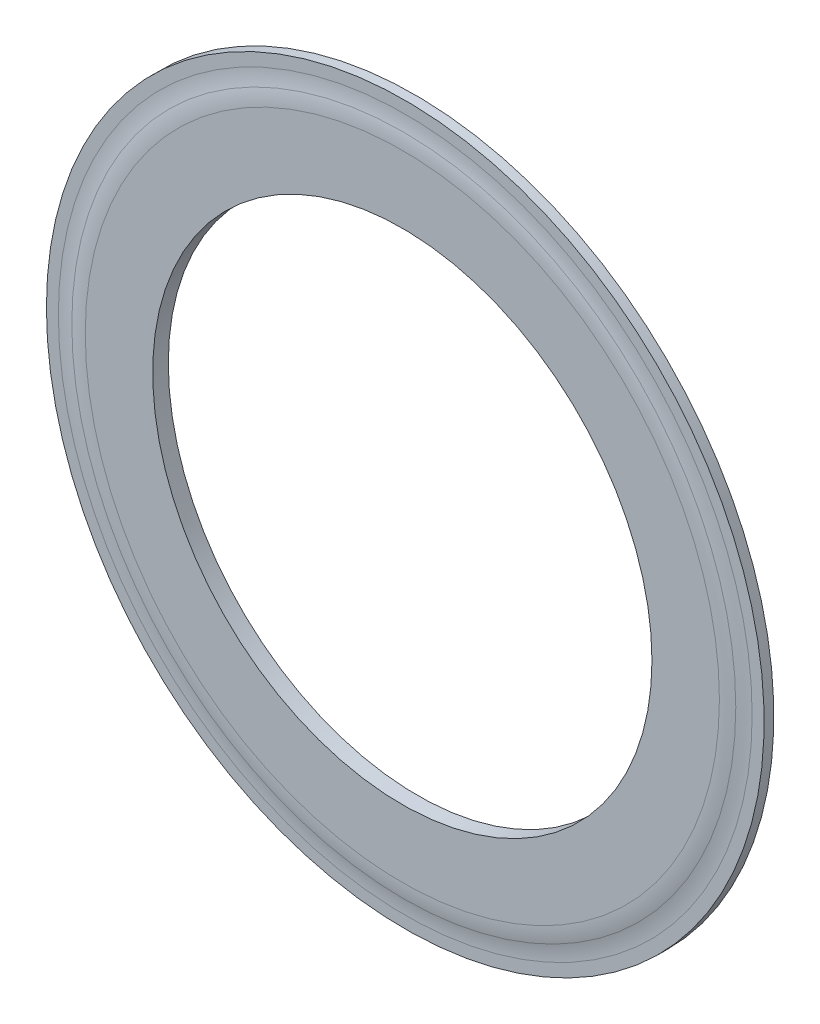
SolidWorks part; units mm, degrees
ref_plane "Front Plane" through (0, 0, 0) normal (0, 0, 1) x (1, 0, 0)
ref_plane "Top Plane" through (0, 0, 0) normal (0, 1, 0) x (1, 0, 0)
ref_plane "Right Plane" through (0, 0, 0) normal (1, 0, 0) x (0, 0, -1)
sketch "Sketch1" plane through (0, 0, 0) normal (0, 0, 1) x (1, 0, 0)
  line L0 (0, 36.5125) -> (0, -36.5125) construction
  line L1 (-36.5125, 0) -> (36.5125, 0) construction
  circle A0 centre (0, 0) radius 36.5125 construction
  circle A1 centre (0, 0) radius 16.2719 construction
  point P8 (0, -16.2719)
  point P9 (16.2719, 0)
  point P10 (0, 16.2719)
  point P11 (-16.2719, 0)
  point P13 (0, 0)
  dimension "OD" = 73.025
  dimension "ID" = 32.5437
  dimension "D1" = 20.2406
sketch "Sketch2" plane through (0, 0, 0) normal (1, 0, 0) x (0, 0, -1)
  line L0 (0, -36.5125) -> (0, 36.5125) construction
  line L1 (0.7938, 36.5125) -> (-0.7938, 36.5125) construction
  line L2 (0.7938, 36.5125) -> (0.7938, -36.5125) construction
  line L3 (0.7938, -36.5125) -> (-0.7938, -36.5125) construction
  line L4 (-0.7938, 36.5125) -> (-0.7938, -36.5125) construction
  line L5 (0.7938, 0) -> (-0.7938, 0) construction
  line L8 (-0.7938, 16.2719) -> (0.7938, 16.2719) construction
  line L9 (-0.7938, -16.2719) -> (0.7938, -16.2719) construction
  point P8 (0, 0)
  dimension "Thickness" = 1.5875
sketch "Sketch3" plane through (0, 0, 0) normal (1, 0, 0) x (0, 0, -1)
  line L0 (0, 16.2719) -> (0, 36.5125) construction
  line L1 (0.4961, 36.5125) -> (-0.4961, 36.5125)
  line L2 (0.4961, 36.5125) -> (0.4961, 16.2719) construction
  line L3 (0.4961, 16.2719) -> (-0.4961, 16.2719)
  line L4 (-0.4961, 36.5125) -> (-0.4961, 16.2719) construction
  line L5 (0.4961, 36.5125) -> (0.4961, 35.2981)
  line L6 (-0.4961, 36.5125) -> (-0.4961, 35.2981)
  line L7 (-0.7938, 36.5125) -> (-0.7938, -36.5125) construction
  line L8 (-0.7938, 32.262) -> (-0.7938, 18.7008)
  line L9 (-0.4961, 17.0815) -> (-0.4961, 16.2719)
  line L10 (-0.7938, 32.262) -> (0, 32.262) construction
  line L11 (-0.4961, 35.2981) -> (0, 35.2981) construction
  line L12 (-0.7938, 18.7008) -> (0, 18.7007) construction
  line L13 (-0.4961, 17.0815) -> (0, 17.0815) construction
  line L14 (0.7938, 32.262) -> (0.7938, 18.7008)
  line L15 (0.4961, 17.0815) -> (0.4961, 16.2719)
  arc A0 (-0.4961, 35.2981) -> (-0.6449, 33.78) centre (-8.3125, 35.2981) cw
  arc A1 (-0.6449, 33.78) -> (-0.7938, 32.262) centre (7.0227, 32.262) ccw
  arc A2 (-0.7938, 18.7008) -> (-0.6449, 17.8911) centre (1.4828, 18.7008) ccw
  arc A3 (-0.6449, 17.8911) -> (-0.4961, 17.0815) centre (-2.7727, 17.0815) cw
  arc A4 (0.4961, 35.2981) -> (0.6449, 33.78) centre (8.3125, 35.2981) ccw
  arc A5 (0.6449, 33.78) -> (0.7938, 32.262) centre (-7.0227, 32.262) cw
  arc A6 (0.7938, 18.7008) -> (0.6449, 17.8911) centre (-1.4828, 18.7008) cw
  arc A7 (0.6449, 17.8911) -> (0.4961, 17.0815) centre (2.7727, 17.0815) ccw
  dimension "D1" = 0.9922
  dimension "D2" = 1.2144
  dimension "D3" = 3.0361
  dimension "D4" = 0.8096
  dimension "D5" = 1.6193
revolve "Revolve1" add sketch "Sketch3" angle 360 about L5
sketch "Sketch4" plane through (0, 0, 0.7938) normal (0, 0, 1) x (1, 0, 0)
  circle A0 centre (0, 0) radius 25.4
  dimension "D1" = 50.8
extrude "Cut-Extrude1" cut sketch "Sketch4" against normal blind 2.54
equation "\"D1@Sketch3\"=\"Thickness@Sketch2\"*.625"
equation "\"D2@Sketch3\"=\"D1@Sketch1\"*.06"
equation "\"D3@Sketch3\"=\"D2@Sketch3\"*2.5"
equation "\"D4@Sketch3\"=\"D1@Sketch1\"*.04"
equation "\"D5@Sketch3\"=\"D4@Sketch3\"*2"
